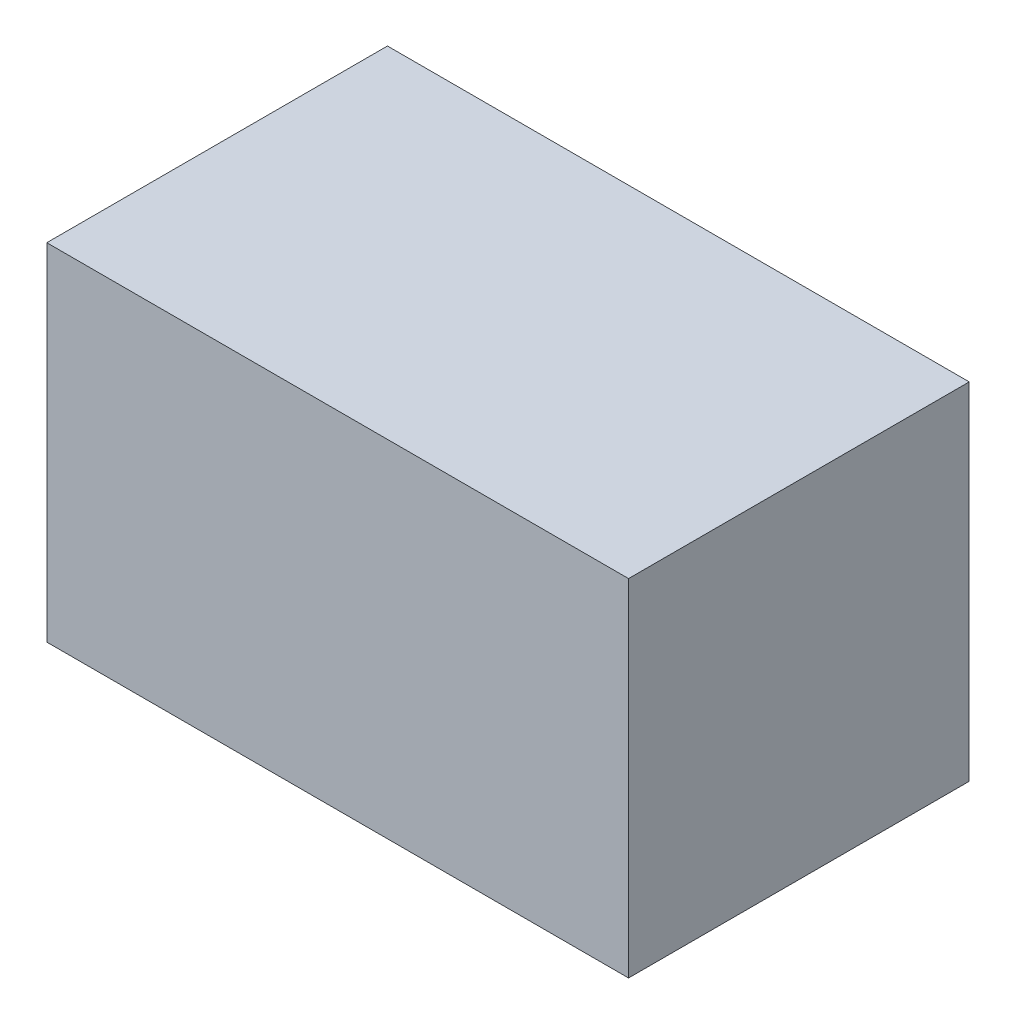
SolidWorks part; units mm, degrees
ref_plane "Спереди" through (0, 0, 0) normal (0, 0, 1) x (1, 0, 0)
ref_plane "Сверху" through (0, 0, 0) normal (0, 1, 0) x (1, 0, 0)
ref_plane "Справа" through (0, 0, 0) normal (1, 0, 0) x (0, 0, -1)
sketch "Эскиз1" plane through (0, 0, 0) normal (0, 1, 0) x (1, 0, 0)
  line L1 (-55.5, -32.5) -> (55.5, -32.5)
  line L2 (-55.5, -32.5) -> (-55.5, 32.5)
  line L3 (-55.5, 32.5) -> (55.5, 32.5)
  line L4 (55.5, -32.5) -> (55.5, 32.5)
  line L5 (0, 32.5) -> (0, -32.5) construction
  line L6 (-55.5, 0) -> (55.5, 0) construction
  point P0 (0, 0)
  dimension "D1" = 111
  dimension "D2" = 65
extrude "Бобышка-Вытянуть1" add sketch "Эскиз1" along normal blind 66
